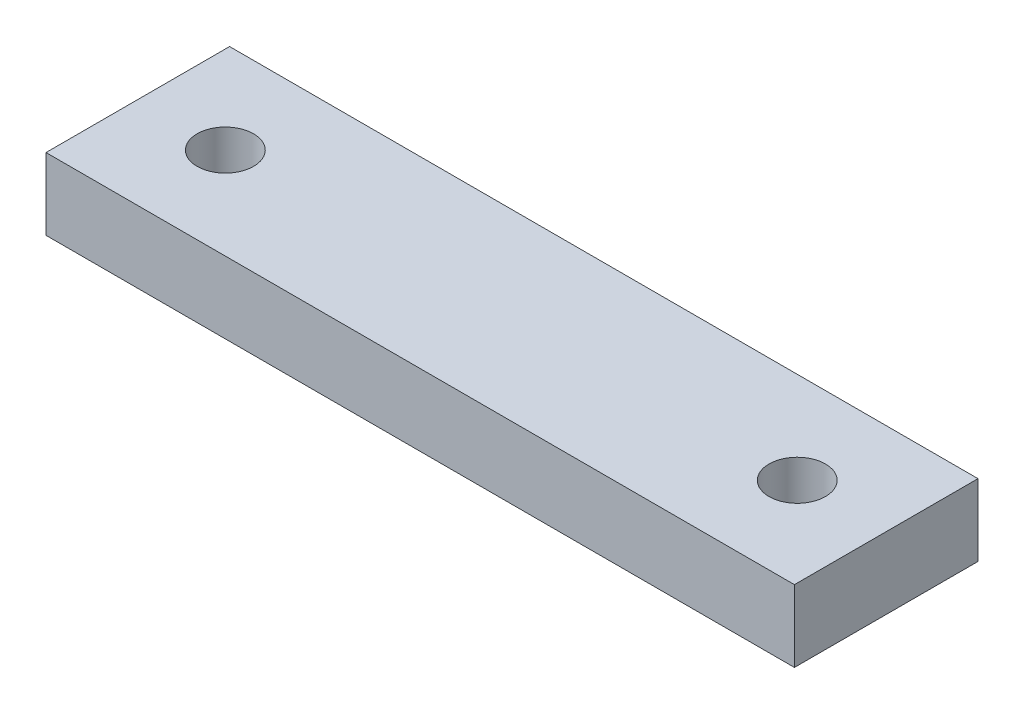
SolidWorks part; units mm, degrees
ref_plane "Front Plane" through (0, 0, 0) normal (0, 0, 1) x (1, 0, 0)
ref_plane "Top Plane" through (0, 0, 0) normal (0, 1, 0) x (1, 0, 0)
ref_plane "Right Plane" through (0, 0, 0) normal (1, 0, 0) x (0, 0, -1)
sketch "Sketch1" plane through (0, 0, 0) normal (0, 1, 0) x (1, 0, 0)
  line L1 (0, 0) -> (26.5, 0)
  line L2 (0, 0) -> (0, 6.5)
  line L3 (0, 6.5) -> (26.5, 6.5)
  line L4 (26.5, 0) -> (26.5, 6.5)
  circle A0 centre (3.1, 3.25) radius 1
  circle A1 centre (23.35, 3.25) radius 1
  dimension "D3" = 2
  dimension "D5" = 2
  dimension "D1" = 26.5
  dimension "D2" = 6.5
  dimension "D4" = 3.1
  dimension "D6" = 3.15
  dimension "D7" = 3.25
  dimension "D8" = 3.25
extrude "Boss-Extrude1" add sketch "Sketch1" along normal blind 2.54
